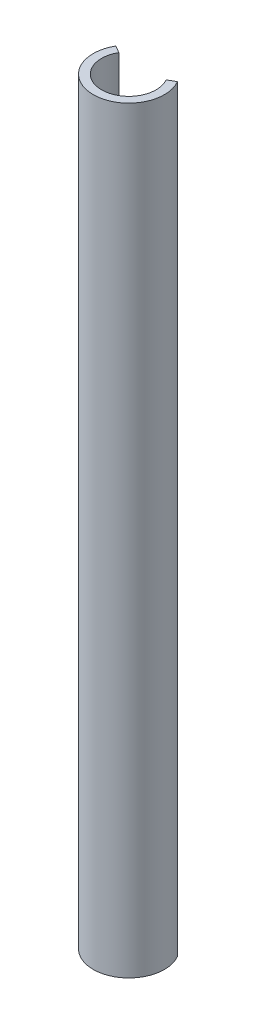
SolidWorks part; units mm, degrees
material "Zoltek Panex 33"
ref_plane "Front Plane" through (0, 0, 0) normal (0, 0, 1) x (1, 0, 0)
ref_plane "Top Plane" through (0, 0, 0) normal (0, 1, 0) x (1, 0, 0)
ref_plane "Right Plane" through (0, 0, 0) normal (1, 0, 0) x (0, 0, -1)
sketch "Sketch1" plane through (0, 0, 0) normal (0, 1, 0) x (1, 0, 0)
  line L4 (0, 0) -> (15.5885, 9) construction
  line L5 (15.5885, 9) -> (20.3516, 11.75)
  line L6 (0, 0) -> (-15.5885, 9) construction
  line L7 (-15.5885, 9) -> (-20.3516, 11.75)
  line L8 (0, 0) -> (0, 15.8551) construction
  arc A0 (-20.3516, 11.75) -> (20.3516, 11.75) centre (0, 0) ccw
  arc A1 (-15.5885, 9) -> (15.5885, 9) centre (0, 0) ccw
  dimension "D1" = 47
  dimension "D2" = 36
  dimension "D3" = 120
  dimension "D4" = 60
extrude "Boss-Extrude1" add sketch "Sketch1" along normal blind 500
sketch "Sketch2" plane through (0, 0, 0) normal (0, 1, 0) x (1, 0, 0)
  line L0 (20.3516, 11.75) -> (-20.3516, 11.75) construction
  line L1 (0, 11.75) -> (0, 6.8158) construction
  point P7 (16.617, 16.617)
  point P8 (16.617, 16.617)
